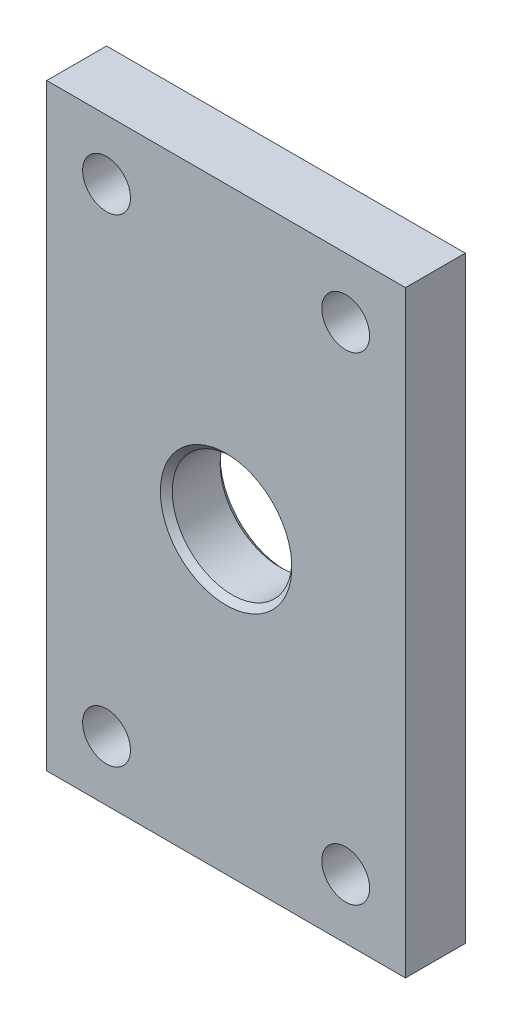
SolidWorks part; units mm, degrees
ref_plane "Front Plane" through (0, 0, 0) normal (1, 0, 0) x (0, 1, 0)
ref_plane "Top Plane" through (0, 0, 0) normal (0, 0, 1) x (0, 1, 0)
ref_plane "Right Plane" through (0, 0, 0) normal (0, 1, 0) x (-1, 0, 0)
sketch "Sketch1" plane through (0, 0, 0) normal (0, 0, 1) x (0, 1, 0)
  line L1 (-50, -30) -> (50, -30)
  line L2 (-50, -30) -> (-50, 30)
  line L3 (-50, 30) -> (50, 30)
  line L4 (50, -30) -> (50, 30)
  line L5 (-50, -30) -> (50, 30) construction
  line L6 (-50, 30) -> (50, -30) construction
  point P0 (0, 0)
  dimension "D1" = 50
  dimension "D2" = 30
extrude "Boss-Extrude1" add sketch "Sketch1" along normal mid plane 10
sketch "Sketch2" plane through (0, 0, 0) normal (0, 0, 1) x (0, 1, 0)
  circle A0 centre (-40, -20) radius 4
  circle A1 centre (40, -20) radius 4
  circle A2 centre (-40, 20) radius 4
  circle A3 centre (40, 20) radius 4
  point P8 (0, 0)
  dimension "D1" = 8
  dimension "D2" = 8
  dimension "D3" = 8
  dimension "D4" = 8
  dimension "D5" = 80
  dimension "D6" = 80
  dimension "D7" = 40
  dimension "D8" = 40
  dimension "D9" = 40
  dimension "D10" = 20
extrude "Cut-Extrude2" cut sketch "Sketch2" against normal through all from offset 5
sketch "Sketch3" plane through (0, 0, 0) normal (0, 0, 1) x (0, 1, 0)
  circle A0 centre (0, 0) radius 10
  point P3 (0, 0)
  dimension "D1" = 20
extrude "Cut-Extrude4" cut sketch "Sketch3" against normal through all from offset 5
chamfer "Chamfer1" distance 1 angle 45 2 edges at (10, 0, -5) (10, 0, 5)
